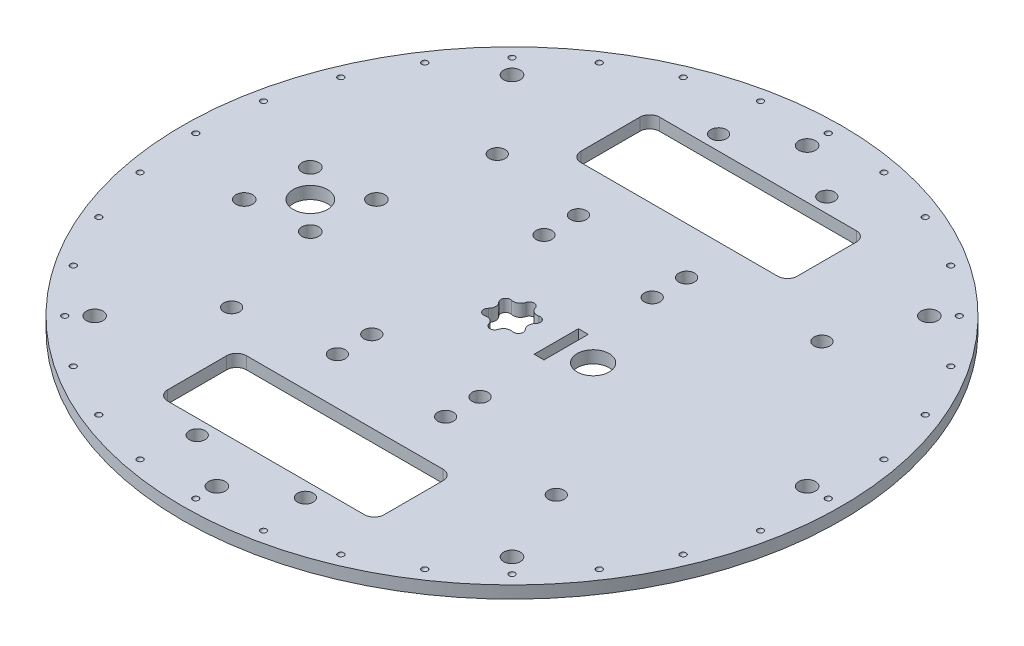
SolidWorks part; units mm, degrees
material "PE High Density"
ref_plane "Front Plane" through (0, 0, 0) normal (0, 0, 1) x (1, 0, 0)
ref_plane "Top Plane" through (0, 0, 0) normal (0, 1, 0) x (1, 0, 0)
ref_plane "Right Plane" through (0, 0, 0) normal (1, 0, 0) x (0, 0, -1)
sketch "Sketch1" plane through (0, 0, 0) normal (0, 1, 0) x (1, 0, 0)
  circle A0 centre (0, 0) radius 67
  dimension "D1" = 134
extrude "Boss-Extrude1" add sketch "Sketch1" along normal mid plane 2.5
sketch "Sketch2" plane through (0, 1.25, 0) normal (0, 1, 0) x (1, 0, 0)
  line L0 (-41, 0) -> (0, 0) construction
  line L1 (-47.7175, -6.7175) -> (-34.2825, 6.7175) construction
  line L2 (-46.6569, 5.6569) -> (-35.3431, -5.6569) construction
  line L3 (0, 57.5) -> (0, 62.5) construction
  circle A0 centre (0, 0) radius 62.5 construction
  circle A1 centre (0, 0) radius 67 construction
  circle A2 centre (0, 0) radius 57.5 construction
  circle A3 centre (-41, 0) radius 13.85 construction
  circle A5 centre (-41, 0) radius 22.5 construction
  circle A6 centre (-42.4264, 42.4264) radius 3 construction
  circle A7 centre (0, 0) radius 63 construction
  point P0 (-11, 17.5)
  point P1 (-11, 24.5)
  point P16 (-11, 53)
  point P17 (0, 60)
  point P20 (-62.5, 0)
  point P21 (-63.5, 0)
  point P23 (42.4264, 42.4264)
  point P24 (60, 0)
  point P25 (42.4264, -42.4264)
  point P26 (0, -60)
  point P27 (-42.4264, -42.4264)
  point P28 (-60, 0)
  point P29 (-42.4264, 42.4264)
  point P30 (0, 0)
  dimension "D4" = 4.5
  dimension "D5" = 5
  dimension "D6" = 27.7
  dimension "D7" = 6
  dimension "D13" = 45
  dimension "D16" = 126
  dimension "D1" = 11
  dimension "D2" = 17.5
  dimension "D3" = 24.5
  dimension "D8" = 41
  dimension "D9" = 45
  dimension "D10" = 53
  dimension "D11" = 9.5
  dimension "D12" = 8
  dimension "D15" = 1
  dimension "D14" = 8
hole_wizard "M3 Clearance Hole1" positions "Sketch3" profile "Sketch4" hole size "M3" standard "ANSI Metric"
sketch "Sketch3" plane through (0, 1.25, 0) normal (0, 1, 0) x (1, 0, 0)
  point P0 (-11, 24.5)
  point P3 (-11, 17.5)
  point P6 (-11, 53)
sketch "Sketch4" plane through (-11, 1.25, -24.5) normal (1, 0, 0) x (0, 0, 1)
  line L0 (0, 0) -> (0, 2.5)
  line L1 (0, 2.5) -> (1.6, 2.5)
  line L2 (1.6, 2.5) -> (1.6, 0)
  line L5 (1.6, 0) -> (0, 0)
  line L11 (0, -6.35) -> (0, 107.95) construction
  dimension "Thru Hole Dia." = 3.2
  dimension "Thru Hole Depth" = 2.5
mirror "Mirror1" about plane through (0, 0, 0) normal (0, 0, 1) of "M3 Clearance Hole1"
sketch "Sketch5" plane through (0, 1.25, 0) normal (0, 1, 0) x (1, 0, 0)
  line L0 (0, 0) -> (67, 0) construction
  line L1 (-22, 34) -> (22, 34)
  line L2 (-22, 34) -> (-22, 50)
  line L3 (-22, 50) -> (22, 50)
  line L4 (22, 34) -> (22, 50)
  line L5 (-22, 34) -> (22, 50) construction
  line L6 (-22, 50) -> (22, 34) construction
  line L7 (-22, -50) -> (22, -50)
  line L8 (22, -34) -> (22, -50)
  line L9 (-22, -34) -> (22, -34)
  line L10 (-22, -34) -> (-22, -50)
  circle A0 centre (0, 0) radius 67 construction
  point P0 (0, 42)
  dimension "D1" = 34
  dimension "D2" = 50
  dimension "D3" = 44
extrude "Cut-Extrude1" cut sketch "Sketch5" against normal through all
fillet "Fillet1" radius 2 8 edges at (22, 0, 34) (22, 0, 50) (-22, 0, 50) (-22, 0, 34) (-22, 0, -34) (22, 0, -50) (22, 0, -34) (-22, 0, -50)
hole_wizard "M3 Clearance Hole2" positions "Sketch6" profile "Sketch7" hole size "M3" standard "ANSI Metric"
sketch "Sketch6" plane through (0, 1.25, 0) normal (0, 1, 0) x (1, 0, 0)
  point P0 (-34.2825, 6.7175)
  point P3 (-35.3431, -5.6569)
  point P6 (-46.6569, 5.6569)
  point P9 (-47.7175, -6.7175)
  point P13 (-42.4264, 42.4264)
  point P16 (0, 60)
  point P19 (42.4264, 42.4264)
  point P22 (60, 0)
  point P25 (42.4264, -42.4264)
  point P28 (0, -60)
  point P31 (-42.4264, -42.4264)
sketch "Sketch7" plane through (-34.2825, 1.25, -6.7175) normal (1, 0, 0) x (0, 0, 1)
  line L0 (0, 0) -> (0, 2.5)
  line L1 (0, 2.5) -> (1.7, 2.5)
  line L2 (1.7, 2.5) -> (1.7, 0)
  line L5 (1.7, 0) -> (0, 0)
  line L11 (0, -6.35) -> (0, 107.95) construction
  dimension "Thru Hole Dia." = 3.4
  dimension "Thru Hole Depth" = 2.5
hole_wizard "Ø7.0 (7) Diameter Hole1" positions "Sketch8" profile "Sketch9" hole size "Ø7.0" standard "ANSI Metric"
sketch "Sketch8" plane through (0, 1.25, 0) normal (0, 1, 0) x (1, 0, 0)
  point P0 (-41, 0)
sketch "Sketch9" plane through (-41, 1.25, 0) normal (1, 0, 0) x (0, 0, 1)
  line L0 (0, 0) -> (0, 2.5)
  line L1 (0, 2.5) -> (3.5, 2.5)
  line L2 (3.5, 2.5) -> (3.5, 0)
  line L5 (3.5, 0) -> (0, 0)
  line L11 (0, -6.35) -> (0, 107.95) construction
  dimension "Thru Hole Dia." = 7
  dimension "Thru Hole Depth" = 2.5
sketch "Sketch10" plane through (0, 1.25, 0) normal (0, 1, 0) x (1, 0, 0)
  line L0 (0, 0) -> (0, 67) construction
  line L1 (0, 0) -> (67, 0) construction
  circle A0 centre (0, 0) radius 57.5 construction
  circle A1 centre (0, 0) radius 67 construction
  circle A2 centre (0, 0) radius 62.5 construction
  circle A3 centre (-41, 0) radius 22.5 construction
  circle A4 centre (-30, 27) radius 4.5 construction
  circle A5 centre (-30, 27) radius 10 construction
  circle A10 centre (-30, -27) radius 10 construction
  circle A11 centre (-30, -27) radius 4.5 construction
  circle A12 centre (36, 27) radius 4.5 construction
  circle A13 centre (36, 27) radius 10 construction
  circle A14 centre (36, -27) radius 4.5 construction
  circle A15 centre (36, -27) radius 10 construction
  dimension "D1" = 5
  dimension "D2" = 4.5
  dimension "D3" = 45
  dimension "D4" = 9
  dimension "D5" = 20
  dimension "D6" = 27
  dimension "D7" = 30
  dimension "D8" = 36
hole_wizard "M3 Clearance Hole3" positions "Sketch13" profile "Sketch12" hole size "M3" standard "ANSI Metric"
sketch "Sketch13" plane through (0, 1.25, 0) normal (0, 1, 0) x (1, 0, 0)
  point P0 (-30, 27)
  point P9 (-30, -27)
  point P14 (36, 27)
  point P17 (36, -27)
sketch "Sketch12" plane through (-30, 1.25, -27) normal (1, 0, 0) x (0, 0, 1)
  line L0 (0, 0) -> (0, 2.5)
  line L1 (0, 2.5) -> (1.6, 2.5)
  line L2 (1.6, 2.5) -> (1.6, 0)
  line L5 (1.6, 0) -> (0, 0)
  line L11 (0, -6.35) -> (0, 107.95) construction
  dimension "Thru Hole Dia." = 3.2
  dimension "Thru Hole Depth" = 2.5
sketch "Sketch14" [suppressed] plane through (0, 1.25, 0) normal (0, 1, 0) x (1, 0, 0)
  line L0 (0, 0) -> (0, 60) construction
  line L1 (0, 0) -> (-42.4264, 42.4264) construction
  line L2 (0, 0) -> (-22.961, 55.4328) construction
  line L3 (0, 0) -> (22.961, 55.4328) construction
  line L4 (0, 0) -> (55.4328, 22.961) construction
  line L5 (0, 0) -> (55.4328, -22.961) construction
  line L6 (0, 0) -> (22.961, -55.4328) construction
  line L7 (0, 0) -> (-22.961, -55.4328) construction
  line L8 (0, 0) -> (-55.4328, -22.961) construction
  line L9 (0, 0) -> (-55.4328, 22.961) construction
  circle A0 centre (0, 0) radius 60 construction
  point P10 (-22.961, 55.4328)
  point P19 (0, 0)
  dimension "D1" = 45
  dimension "D2" = 22.5
  dimension "D3" = 8
hole_wizard "M3 Clearance Hole4" [suppressed] positions "Sketch17" profile "Sketch16" hole size "M3" standard "ANSI Metric"
sketch "Sketch17" [suppressed] plane through (0, 1.25, 0) normal (0, 1, 0) x (1, 0, 0)
  point P0 (-22.961, 55.4328)
  point P3 (22.961, 55.4328)
  point P6 (55.4328, 22.961)
  point P9 (55.4328, -22.961)
  point P12 (22.961, -55.4328)
  point P15 (-22.961, -55.4328)
  point P18 (-55.4328, -22.961)
  point P21 (-55.4328, 22.961)
sketch "Sketch16" plane through (-22.961, 1.25, -55.4328) normal (1, 0, 0) x (0, 0, 1)
  line L0 (0, 0) -> (0, 2.5)
  line L1 (0, 2.5) -> (1.6, 2.5)
  line L2 (1.6, 2.5) -> (1.6, 0)
  line L5 (1.6, 0) -> (0, 0)
  line L11 (0, -6.35) -> (0, 107.95) construction
  dimension "Thru Hole Dia." = 3.2
  dimension "Thru Hole Depth" = 2.5
sketch "Sketch18" plane through (0, 1.25, 0) normal (0, 1, 0) x (1, 0, 0)
  line L1 (9, -4.5) -> (11, -4.5)
  line L2 (9, -4.5) -> (9, 4.5)
  line L3 (9, 4.5) -> (11, 4.5)
  line L4 (11, -4.5) -> (11, 4.5)
  line L5 (9, -4.5) -> (11, 4.5) construction
  line L6 (9, 4.5) -> (11, -4.5) construction
  circle A0 centre (16.5, 0) radius 3.25
  point P0 (10, 0)
  dimension "D4" = 6.5
  dimension "D1" = 9
  dimension "D2" = 2
  dimension "D3" = 5.5
  dimension "D5" = 10
extrude "Cut-Extrude2" cut sketch "Sketch18" against normal through all
sketch "Sketch19" plane through (0, 1.25, 0) normal (0, 1, 0) x (1, 0, 0)
  circle A0 centre (0, 0) radius 2.5
  arc A1 (0.9633, 3.7685) -> (-0.9633, 3.7685) centre (0, 3.5) ccw
  arc A2 (3.7452, 1.05) -> (2.7819, 2.7185) centre (3.0311, 1.75) ccw
  arc A3 (2.7819, -2.7185) -> (3.7452, -1.05) centre (3.0311, -1.75) ccw
  arc A4 (-0.9633, -3.7685) -> (0.9633, -3.7685) centre (0, -3.5) ccw
  arc A5 (-3.7452, -1.05) -> (-2.7819, -2.7185) centre (-3.0311, -1.75) ccw
  arc A6 (-2.7819, 2.7185) -> (-3.7452, 1.05) centre (-3.0311, 1.75) ccw
  arc A7 (-2.7819, 2.7185) -> (-0.9633, 3.7685) centre (-2.4082, 4.1712) ccw
  arc A8 (0.9633, 3.7685) -> (2.7819, 2.7185) centre (2.4082, 4.1712) ccw
  arc A9 (3.7452, 1.05) -> (3.7452, -1.05) centre (4.8164, 0) ccw
  arc A10 (2.7819, -2.7185) -> (0.9633, -3.7685) centre (2.4082, -4.1712) ccw
  arc A11 (-0.9633, -3.7685) -> (-2.7819, -2.7185) centre (-2.4082, -4.1712) ccw
  arc A12 (-3.7452, -1.05) -> (-3.7452, 1.05) centre (-4.8164, 0) ccw
  arc A13 (-3.7452, 1.05) -> (-2.1651, 1.25) centre (-3.0311, 1.75) ccw construction
  arc A14 (-2.1651, 1.25) -> (-2.7819, 2.7185) centre (-3.0311, 1.75) ccw construction
  arc A15 (-0.9633, 3.7685) -> (0, 2.5) centre (0, 3.5) ccw construction
  arc A16 (0, 2.5) -> (0.9633, 3.7685) centre (0, 3.5) ccw construction
  arc A17 (2.7819, 2.7185) -> (2.1651, 1.25) centre (3.0311, 1.75) ccw construction
  arc A18 (2.1651, 1.25) -> (3.7452, 1.05) centre (3.0311, 1.75) ccw construction
  arc A19 (3.7452, -1.05) -> (2.1651, -1.25) centre (3.0311, -1.75) ccw construction
  arc A20 (2.1651, -1.25) -> (2.7819, -2.7185) centre (3.0311, -1.75) ccw construction
  arc A21 (0.9633, -3.7685) -> (0, -2.5) centre (0, -3.5) ccw construction
  arc A22 (0, -2.5) -> (-0.9633, -3.7685) centre (0, -3.5) ccw construction
  arc A23 (-2.7819, -2.7185) -> (-2.1651, -1.25) centre (-3.0311, -1.75) ccw construction
  arc A24 (-2.1651, -1.25) -> (-3.7452, -1.05) centre (-3.0311, -1.75) ccw construction
  point P17 (0, 0)
  point P36 (0, 0)
  dimension "D1" = 5
  dimension "D2" = 2
  dimension "D4" = 1.5
  dimension "D3" = 6
  dimension "D5" = 6
extrude "Cut-Extrude3" cut sketch "Sketch19" against normal through all contours A0 | A12 A5 A11 A4 A10 A3 A9 A2 A8 A1 A7 A6 A0
sketch "Sketch20" plane through (0, 1.25, 0) normal (0, 1, 0) x (1, 0, 0)
  line L0 (0, 64.9) -> (0, 63.7)
  arc A0 (0, 63.7) -> (0, 64.9) centre (0, 64.3) ccw
  circle A1 centre (0, 0) radius 61.7 construction
  circle A2 centre (0, 60) radius 1.7 construction
  circle A3 centre (0, 0) radius 67 construction
  arc A4 (0, 64.9) -> (0, 63.7) centre (0, 64.3) ccw construction
  point P9 (0, 67)
  dimension "D1" = 1.2
  dimension "D2" = 5.3
  dimension "D3" = 2.7
revolve "Cut-Revolve1" cut sketch "Sketch20" angle 360 about L0
pattern_circular "CirPattern1" count 32 over 360 about axis through (0, 0, 0) along (0, 1, 0) of "Cut-Revolve1"
equation "\"D2@Sketch14\"=\"D1@Sketch14\"/2"
